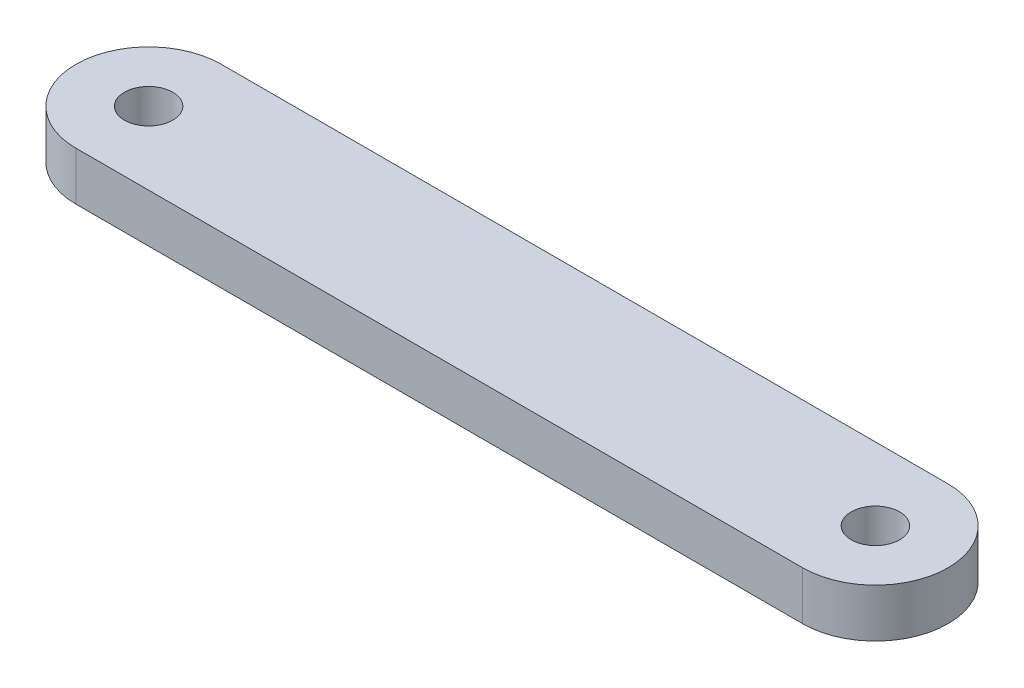
SolidWorks part; units mm, degrees
ref_plane "Front Plane" through (0, 0, 0) normal (0, 0, 1) x (1, 0, 0)
ref_plane "Top Plane" through (0, 0, 0) normal (0, 1, 0) x (1, 0, 0)
ref_plane "Right Plane" through (0, 0, 0) normal (1, 0, 0) x (0, 0, -1)
sketch "Sketch1" plane through (0, 0, 0) normal (0, 1, 0) x (1, 0, 0)
  line L1 (-37.5, 7.5) -> (37.5, 7.5)
  line L3 (-37.5, -7.5) -> (37.5, -7.5)
  line L5 (-37.5, 7.5) -> (37.5, -7.5) construction
  line L6 (-37.5, -7.5) -> (37.5, 7.5) construction
  arc A0 (37.5, 7.5) -> (37.5, -7.5) centre (37.5, 0) cw
  arc A1 (-37.5, 7.5) -> (-37.5, -7.5) centre (-37.5, 0) ccw
  circle A2 centre (37.5, 0) radius 2.5
  circle A3 centre (-37.5, 0) radius 2.5
  point P0 (0, 0)
  dimension "D3" = 5
  dimension "D4" = 5
  dimension "D1" = 75
  dimension "D2" = 15
extrude "Boss-Extrude1" add sketch "Sketch1" along normal blind 5
